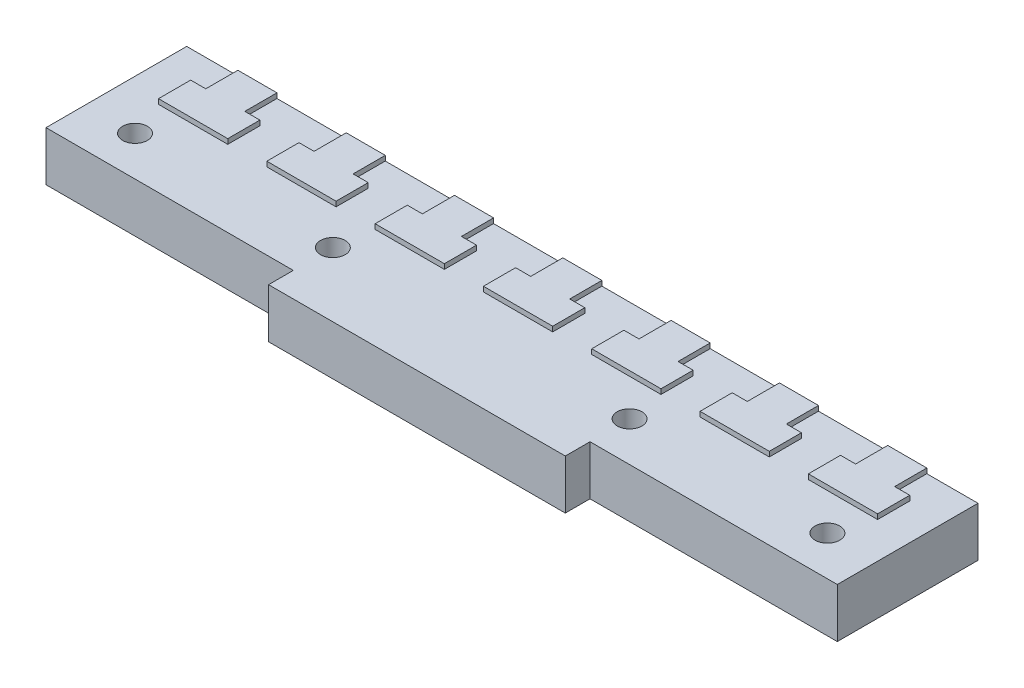
SolidWorks part; units mm, degrees
ref_plane "Front Plane" through (0, 0, 0) normal (0, 0, 1) x (1, 0, 0)
ref_plane "Top Plane" through (0, 0, 0) normal (0, 1, 0) x (1, 0, 0)
ref_plane "Right Plane" through (0, 0, 0) normal (1, 0, 0) x (0, 0, -1)
sketch "Sketch2" plane through (0, 0, 0) normal (0, 1, 0) x (1, 0, 0)
  line L1 (-80, -14.225) -> (80, -14.225)
  line L2 (-80, -14.225) -> (-80, 14.225)
  line L3 (-80, 14.225) -> (80, 14.225)
  line L4 (80, -14.225) -> (80, 14.225)
  line L5 (-80, -14.225) -> (80, 14.225) construction
  line L6 (-80, 14.225) -> (80, -14.225) construction
  point P0 (0, 0)
  dimension "D1" = 28.45
  dimension "D2" = 160
extrude "Boss-Extrude1" add sketch "Sketch2" along normal blind 10
sketch "Sketch4" plane through (0, 0, 14.225) normal (0, 0, 1) x (1, 0, 0)
  line L0 (0, 10) -> (0, 0) construction
  line L1 (-80, 10) -> (80, 10) construction
  line L2 (-80, 0) -> (80, 0) construction
  line L4 (-30, 10) -> (30, 10)
  line L5 (-30, 10) -> (-30, 0)
  line L6 (-30, 0) -> (30, 0)
  line L7 (30, 10) -> (30, 0)
  point P10 (0, 10)
  dimension "D1" = 60
extrude "Boss-Extrude2" add sketch "Sketch4" along normal blind 5
sketch "Sketch5" plane through (0, 10, 0) normal (0, 1, 0) x (1, 0, 0)
  line L0 (80, -6.225) -> (-80, -6.225) construction
  line L1 (80, -14.225) -> (80, 14.225) construction
  line L2 (-80, 14.225) -> (-80, -14.225) construction
  line L3 (0, -19.225) -> (0, 14.225) construction
  line L4 (30, -19.225) -> (-30, -19.225) construction
  line L5 (80, 14.225) -> (-80, 14.225) construction
  line L6 (30, -14.225) -> (80, -14.225) construction
  circle A0 centre (70, -6.225) radius 2.5
  circle A1 centre (30, -6.225) radius 2.5
  circle A2 centre (-30, -6.225) radius 2.5
  circle A3 centre (-70, -6.225) radius 2.5
  dimension "D1" = 5
  dimension "D2" = 40
  dimension "D3" = 10
  dimension "D4" = 8
extrude "Cut-Extrude1" cut sketch "Sketch5" against normal through all
sketch "Sketch6" plane through (0, 10, 0) normal (0, 1, 0) x (1, 0, 0)
  line L0 (0, -19.225) -> (0, 14.225) construction
  line L1 (30, -19.225) -> (-30, -19.225) construction
  line L2 (80, 14.225) -> (-80, 14.225) construction
  line L3 (3.95, 14.225) -> (3.95, 7.725)
  line L4 (3.95, 7.725) -> (7, 7.725)
  line L5 (7, 7.725) -> (7, 1.225)
  line L6 (7, 1.225) -> (0, 1.225)
  line L7 (-3.95, 14.225) -> (-3.95, 7.725)
  line L8 (-3.95, 7.725) -> (-7, 7.725)
  line L9 (-7, 7.725) -> (-7, 1.225)
  line L10 (-7, 1.225) -> (0, 1.225)
  line L11 (3.95, 14.225) -> (-3.95, 14.225)
  line L12 (-17.95, 14.225) -> (-25.85, 14.225)
  line L13 (-17.95, 14.225) -> (-17.95, 7.725)
  line L14 (-25.85, 14.225) -> (-25.85, 7.725)
  line L15 (-25.85, 7.725) -> (-28.9, 7.725)
  line L16 (-28.9, 7.725) -> (-28.9, 1.225)
  line L17 (-17.95, 7.725) -> (-14.9, 7.725)
  line L18 (-14.9, 7.725) -> (-14.9, 1.225)
  line L19 (-14.9, 1.225) -> (-21.9, 1.225)
  line L20 (-28.9, 1.225) -> (-21.9, 1.225)
  line L21 (-39.85, 14.225) -> (-47.75, 14.225)
  line L22 (-39.85, 14.225) -> (-39.85, 7.725)
  line L23 (-47.75, 14.225) -> (-47.75, 7.725)
  line L24 (-47.75, 7.725) -> (-50.8, 7.725)
  line L25 (-50.8, 7.725) -> (-50.8, 1.225)
  line L26 (-39.85, 7.725) -> (-36.8, 7.725)
  line L27 (-36.8, 7.725) -> (-36.8, 1.225)
  line L28 (-36.8, 1.225) -> (-43.8, 1.225)
  line L29 (-50.8, 1.225) -> (-43.8, 1.225)
  line L30 (-61.75, 14.225) -> (-69.65, 14.225)
  line L31 (-61.75, 14.225) -> (-61.75, 7.725)
  line L32 (-69.65, 14.225) -> (-69.65, 7.725)
  line L33 (-69.65, 7.725) -> (-72.7, 7.725)
  line L34 (-72.7, 7.725) -> (-72.7, 1.225)
  line L35 (-61.75, 7.725) -> (-58.7, 7.725)
  line L36 (-58.7, 7.725) -> (-58.7, 1.225)
  line L37 (-58.7, 1.225) -> (-65.7, 1.225)
  line L38 (-72.7, 1.225) -> (-65.7, 1.225)
  line L39 (25.85, 14.225) -> (17.95, 14.225)
  line L40 (17.95, 14.225) -> (17.95, 7.725)
  line L41 (25.85, 14.225) -> (25.85, 7.725)
  line L42 (25.85, 7.725) -> (28.9, 7.725)
  line L43 (17.95, 7.725) -> (14.9, 7.725)
  line L44 (14.9, 7.725) -> (14.9, 1.225)
  line L45 (28.9, 7.725) -> (28.9, 1.225)
  line L46 (28.9, 1.225) -> (21.9, 1.225)
  line L47 (14.9, 1.225) -> (21.9, 1.225)
  line L48 (47.75, 14.225) -> (39.85, 14.225)
  line L49 (39.85, 14.225) -> (39.85, 7.725)
  line L50 (47.75, 14.225) -> (47.75, 7.725)
  line L51 (47.75, 7.725) -> (50.8, 7.725)
  line L52 (39.85, 7.725) -> (36.8, 7.725)
  line L53 (36.8, 7.725) -> (36.8, 1.225)
  line L54 (50.8, 7.725) -> (50.8, 1.225)
  line L55 (50.8, 1.225) -> (43.8, 1.225)
  line L56 (36.8, 1.225) -> (43.8, 1.225)
  line L57 (69.65, 14.225) -> (61.75, 14.225)
  line L58 (61.75, 14.225) -> (61.75, 7.725)
  line L59 (69.65, 14.225) -> (69.65, 7.725)
  line L60 (69.65, 7.725) -> (72.7, 7.725)
  line L61 (61.75, 7.725) -> (58.7, 7.725)
  line L62 (58.7, 7.725) -> (58.7, 1.225)
  line L63 (72.7, 7.725) -> (72.7, 1.225)
  line L64 (72.7, 1.225) -> (65.7, 1.225)
  line L65 (58.7, 1.225) -> (65.7, 1.225)
  dimension "D1" = 7.9
  dimension "D2" = 6.5
  dimension "D3" = 6.5
  dimension "D4" = 14
  dimension "D6" = 14
  dimension "D8" = 14
  dimension "D5" = 4
  dimension "D7" = 4
extrude "Boss-Extrude3" add sketch "Sketch6" along normal blind 1
